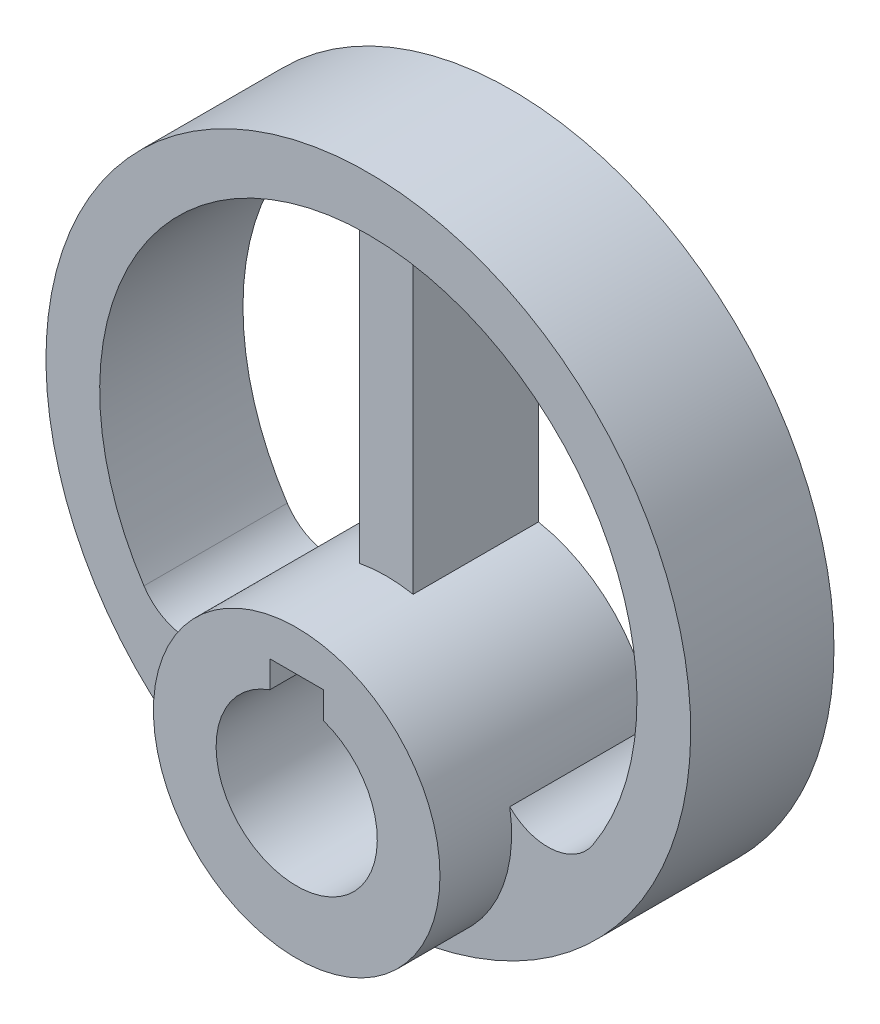
SolidWorks part; units mm, degrees
ref_plane "Front Plane" through (0, 0, 0) normal (0, 0, 1) x (1, 0, 0)
ref_plane "Top Plane" through (0, 0, 0) normal (0, 1, 0) x (1, 0, 0)
ref_plane "Right Plane" through (0, 0, 0) normal (1, 0, 0) x (0, 0, -1)
sketch "Sketch1" plane through (0, 0, 0) normal (0, 0, 1) x (1, 0, 0)
  line L0 (-80.5754, 0) -> (87.1927, 0) construction
  line L1 (0, 62.494) -> (0, -89.5282) construction
  line L3 (-4.7625, -13.5171) -> (4.7625, -13.5171)
  line L4 (-4.7625, -13.5171) -> (-4.7625, -18.2796)
  line L6 (4.7625, -13.5171) -> (4.7625, -18.2796)
  circle A0 centre (0, 0) radius 57.15
  arc A1 (-39.7791, -26.1871) -> (47.625, 0) centre (0, 0) cw
  arc A2 (-4.7625, -18.2796) -> (4.7625, -18.2796) centre (0, -31.75) ccw
  arc A3 (25.0696, -27.6663) -> (-25.0696, -27.6663) centre (0, -31.75) ccw
  arc A4 (-25.0696, -27.6663) -> (-39.7791, -26.1871) centre (-31.8233, -20.9497) cw
  arc A5 (25.0696, -27.6663) -> (39.7791, -26.1871) centre (31.8233, -20.9497) ccw
  arc A6 (39.7791, -26.1871) -> (-47.625, 0) centre (0, 0) ccw
  point P15 (0, -17.4625)
  point P16 (0, -13.5171)
  dimension "D1" = 28.575
  dimension "D2" = 50.8
  dimension "D3" = 9.525
  dimension "D4" = 114.3
  dimension "D5" = 9.525
  dimension "D8" = 31.8233
  dimension "D6" = 4.7625
  dimension "D7" = 9.525
extrude "Boss-Extrude5" add sketch "Sketch1" along normal blind 25.4 contours A0 A6 A5 A3 A4 A1 A2 L4 L3 L6
sketch "Sketch4" plane through (0, 0, 25.4) normal (0, 0, 1) x (1, 0, 0)
  line L0 (-4.7625, -18.2796) -> (-4.7625, -13.5171)
  line L1 (-4.7625, -13.5171) -> (4.7625, -13.5171)
  line L2 (4.7625, -13.5171) -> (4.7625, -18.2796)
  circle A0 centre (0, -31.75) radius 25.4
  arc A1 (-4.7625, -18.2796) -> (4.7625, -18.2796) centre (0, -31.75) ccw
extrude "Boss-Extrude7" add sketch "Sketch4" along normal blind 12.7
sketch "Sketch5" plane through (0, 0, 0) normal (0, 0, 1) x (1, 0, 0)
  line L0 (0, -35.0965) -> (0, 70.9679) construction
  line L1 (-4.7625, -7.6714) -> (4.7625, -7.6714)
  line L2 (-4.7625, -7.6714) -> (-4.7625, 48.7767)
  line L3 (-4.7625, 48.7767) -> (4.7625, 48.7767)
  line L4 (4.7625, -7.6714) -> (4.7625, 48.7767)
  point P6 (0, 48.7767)
  dimension "D1" = 9.525
extrude "Boss-Extrude8" add sketch "Sketch5" along normal blind 22.225
